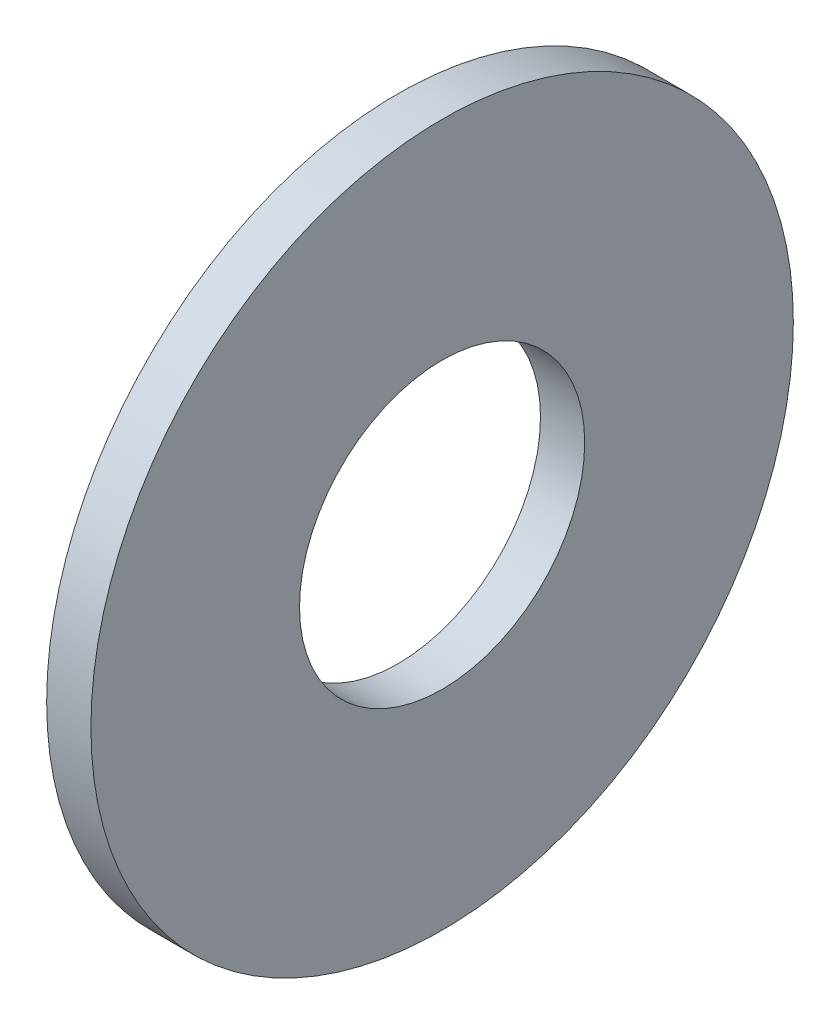
SolidWorks part; units mm, degrees
material "SAE 1020"
ref_plane "Plane1" through (0, 0, 0) normal (0, 0, 1) x (1, 0, 0)
ref_plane "Plane2" through (0, 0, 0) normal (0, 1, 0) x (1, 0, 0)
ref_plane "Plane3" through (0, 0, 0) normal (1, 0, 0) x (0, 0, -1)
sketch "Sketch1" plane through (0, 0, 0) normal (0, 0, 1) x (1, 0, 0)
  line L0 (-34.925, 0) -> (9.525, 0) construction
  line L1 (0, 5.1562) -> (0, 12.7)
  line L2 (0, 12.7) -> (-1.6002, 12.7)
  line L3 (-1.6002, 12.7) -> (-1.6002, 5.1562)
  line L4 (-1.6002, 5.1562) -> (0, 5.1562)
  dimension "Thickness" = 1.6002
  dimension "Inside_dia" = 10.3124
  dimension "Outside_dia" = 25.4
revolve "Base-Revolve" add sketch "Sketch1" angle 360 about L0
